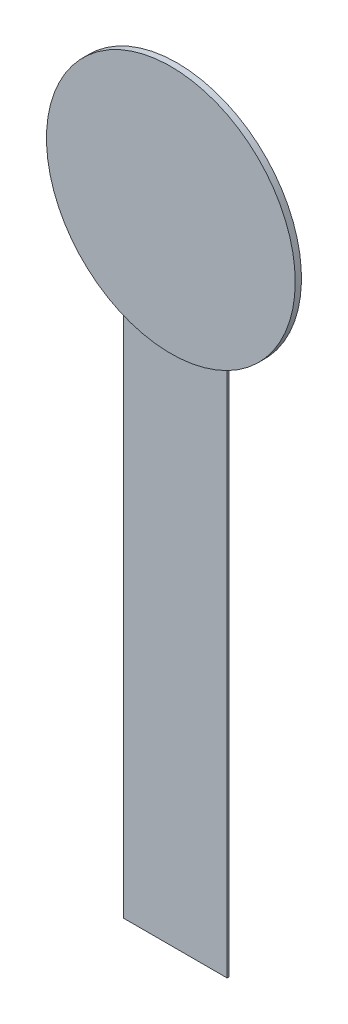
SolidWorks part; units mm, degrees
ref_plane "Front Plane" through (0, 0, 0) normal (0, 0, 1) x (1, 0, 0)
ref_plane "Top Plane" through (0, 0, 0) normal (0, 1, 0) x (1, 0, 0)
ref_plane "Right Plane" through (0, 0, 0) normal (1, 0, 0) x (0, 0, -1)
sketch "Sketch1" plane through (0, 0, 0) normal (0, 0, 1) x (1, 0, 0)
  line L0 (0, 0) -> (0, -47.19) construction
  line L1 (-3.81, -47.19) -> (-3.81, -8.319) construction
  line L2 (3.81, -8.319) -> (3.81, -47.19) construction
  line L3 (-3.81, -47.19) -> (3.81, -47.19) construction
  line L4 (0, 9.15) -> (0, 0) construction
  line L5 (0, 0) -> (9.15, 0) construction
  circle A0 centre (0, 0) radius 9.15
  circle A1 centre (0, 0) radius 7.34 construction
  dimension "D1" = 14.68
  dimension "D2" = 18.3
  dimension "D3" = 7.62
  dimension "D4" = 56.34
extrude "Boss-Extrude1" add sketch "Sketch1" along normal blind 0.46
sketch "Sketch2" plane through (0, 0, 0) normal (0, 0, 1) x (1, 0, 0)
  line L0 (-3.81, -47.19) -> (3.81, -47.19)
  line L1 (3.81, -47.19) -> (3.81, -8.319)
  line L2 (3.81, -8.319) -> (-3.81, -8.319)
  line L3 (-3.81, -8.319) -> (-3.81, -47.19)
extrude "Boss-Extrude2" add sketch "Sketch2" along normal blind 0.13
